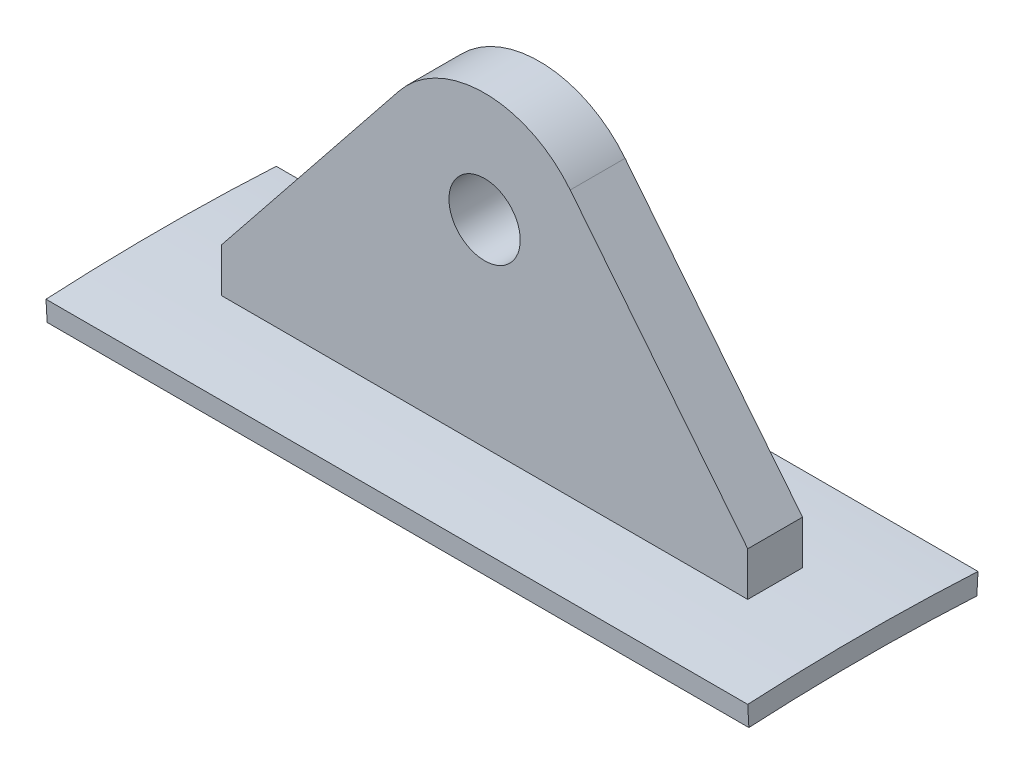
SolidWorks part; units mm, degrees
material "ASTM A36 Steel"
ref_plane "Front Plane" through (0, 0, 0) normal (0, 0, 1) x (1, 0, 0)
ref_plane "Top Plane" through (0, 0, 0) normal (0, 1, 0) x (1, 0, 0)
ref_plane "Right Plane" through (0, 0, 0) normal (1, 0, 0) x (0, 0, -1)
sketch "Sketch1" plane through (0, 0, 0) normal (0, 0, 1) x (1, 0, 0)
  line L0 (-152.4, 0) -> (152.4, 0)
  line L1 (-152.4, 0) -> (-152.4, 25.4)
  line L2 (152.4, 0) -> (152.4, 25.4)
  line L3 (0, 0) -> (0, 177.8) construction
  line L4 (-152.4, 25.4) -> (-49.5926, 153.9588)
  line L5 (152.4, 25.4) -> (49.5926, 153.9588)
  circle A0 centre (0, 114.3) radius 20.6375
  arc A1 (49.5926, 153.9588) -> (-49.5926, 153.9588) centre (0, 114.3) ccw
  point P4 (0, 0)
  point P9 (-6.5098, 161.1937)
  point P13 (0, 0)
  point P14 (0, 0)
  dimension "D3" = 41.275
  dimension "D4" = 63.5
  dimension "D1" = 304.8
  dimension "D2" = 25.4
  dimension "D5" = 177.8
extrude "Boss-Extrude4" add sketch "Sketch1" along normal blind 31.75
sketch "Sketch5" plane through (0, 0, 0) normal (1, 0, 0) x (0, 0, -1)
  line L0 (-15.875, 0) -> (-15.875, -12) construction
  line L1 (-31.75, 0) -> (0, 0) construction
  line L5 (-15.875, -12) -> (-15.875, -1215.2) construction
  line L6 (-15.875, -1215.2) -> (-82.55, -1.8305)
  line L7 (-15.875, -1215.2) -> (50.8, -1.8305)
  arc A0 (50.1416, -13.8124) -> (-81.8916, -13.8124) centre (-15.875, -1215.2) ccw
  arc A1 (50.8, -1.8305) -> (-82.55, -1.8305) centre (-15.875, -1215.2) ccw
  circle A2 centre (-15.875, -1215.2) radius 1215.2 construction
  circle A3 centre (-15.875, -1215.2) radius 1203.2 construction
  dimension "D4" = 66.675
  dimension "D1" = 12
  dimension "D3" = 12
  dimension "D2" = 1203.2
extrude "Boss-Extrude6" add sketch "Sketch5" along normal mid plane 406.4 separate body contours L7 A1 L6 A0
